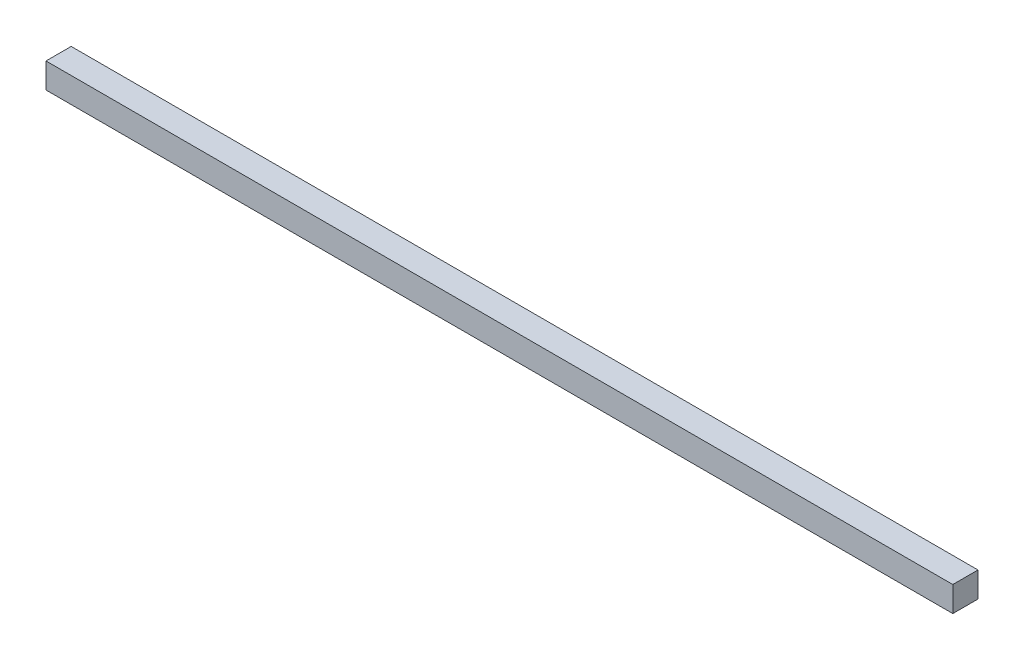
SolidWorks part; units mm, degrees
material "Oak"
ref_plane "Front" through (0, 0, 0) normal (0, 0, 1) x (1, 0, 0)
ref_plane "Top" through (0, 0, 0) normal (0, 1, 0) x (1, 0, 0)
ref_plane "Right" through (0, 0, 0) normal (1, 0, 0) x (0, 0, -1)
sketch "Sketch1" plane through (0, 0, 0) normal (0, 0, 1) x (1, 0, 0)
  line L1 (-4572, -127) -> (4572, -127)
  line L2 (-4572, -127) -> (-4572, 127)
  line L3 (-4572, 127) -> (4572, 127)
  line L4 (4572, -127) -> (4572, 127)
  line L5 (-4572, -127) -> (4572, 127) construction
  line L6 (-4572, 127) -> (4572, -127) construction
  point P0 (0, 0)
  dimension "D1" = 9144
  dimension "D2" = 254
extrude "Boss-Extrude1" add sketch "Sketch1" along normal blind 254
